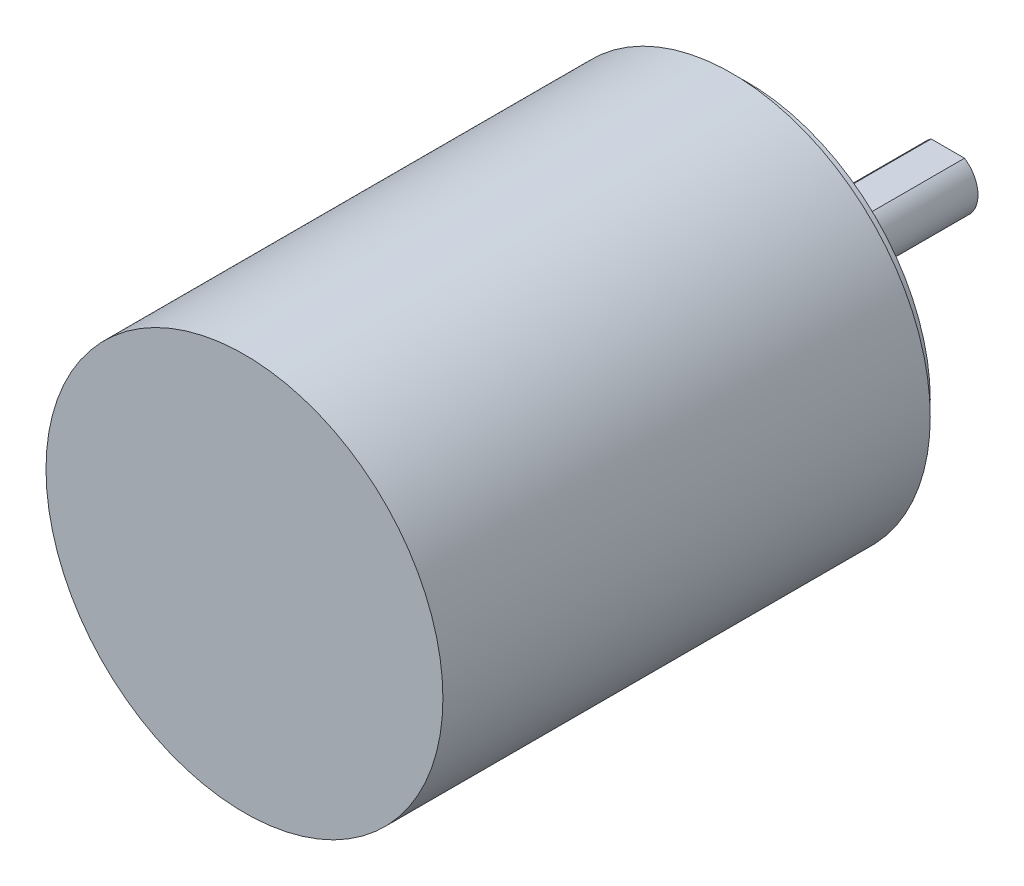
SolidWorks part; units mm, degrees
ref_plane "前视基准面" through (0, 0, 0) normal (0, 0, 1) x (1, 0, 0)
ref_plane "上视基准面" through (0, 0, 0) normal (0, 1, 0) x (1, 0, 0)
ref_plane "右视基准面" through (0, 0, 0) normal (1, 0, 0) x (0, 0, -1)
other "Configuration Table"
sketch "草图1" plane through (0, 0, 0) normal (1, 0, 0) x (0, 0, -1)
  line L0 (-105, 0) -> (45, 0) construction
  line L1 (40, 0) -> (40, 6)
  line L2 (40, 6) -> (0, 6)
  line L3 (0, 6) -> (0, 36.5)
  line L4 (0, 36.5) -> (-3, 36.5)
  line L5 (-3, 36.5) -> (-3, 39.5)
  line L6 (-3, 39.5) -> (-100, 39.5)
  line L7 (-100, 39.5) -> (-100, 0)
  line L8 (-100, 0) -> (40, 0)
revolve "旋转1" add sketch "草图1" angle 360 about L0
sketch "草图2" plane through (0, 0, 0) normal (0, 0, 1) x (1, 0, 0)
  line L1 (-8, 5) -> (8, 5)
  line L2 (-8, 5) -> (-8, 10)
  line L3 (-8, 10) -> (8, 10)
  line L4 (8, 5) -> (8, 10)
extrude "切除-拉伸4" cut sketch "草图2" against normal blind 29 from offset 11
